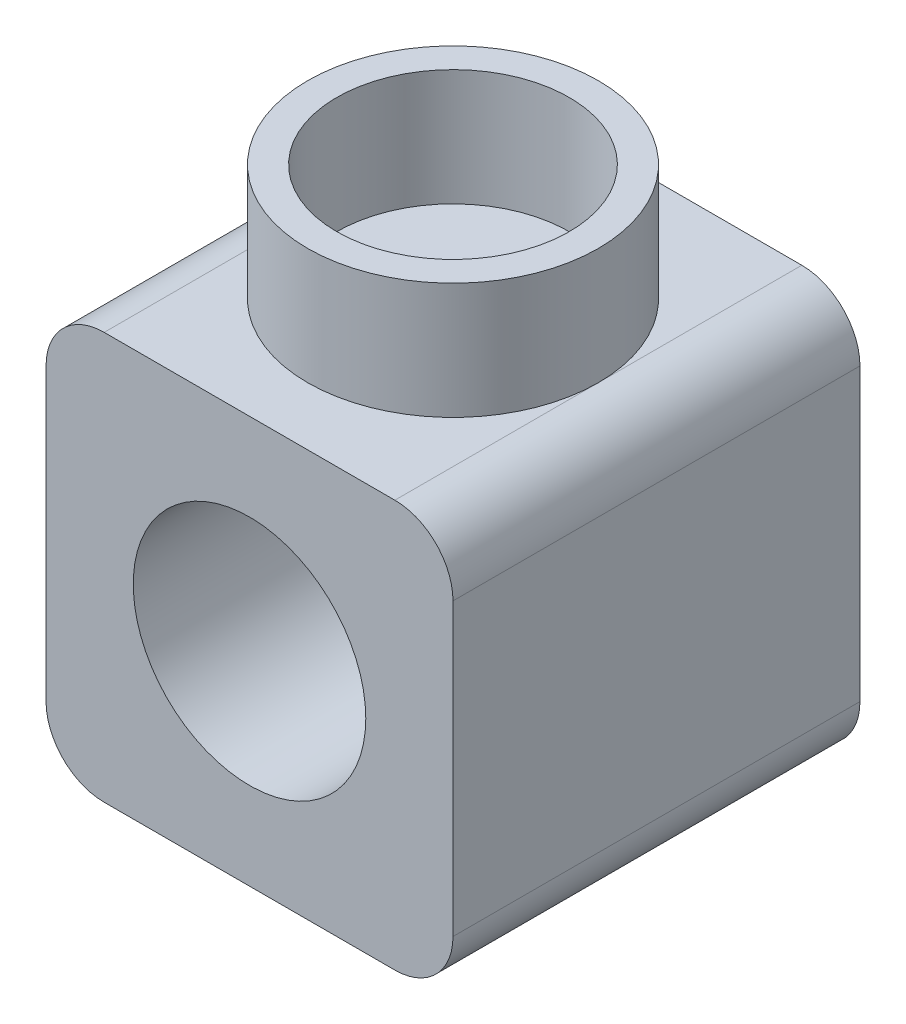
SolidWorks part; units mm, degrees
ref_plane "Front Plane" through (0, 0, 0) normal (0, 0, 1) x (1, 0, 0)
ref_plane "Top Plane" through (0, 0, 0) normal (0, 1, 0) x (1, 0, 0)
ref_plane "Right Plane" through (0, 0, 0) normal (1, 0, 0) x (0, 0, -1)
sketch "Sketch1" plane through (0, 0, 0) normal (0, 0, 1) x (1, 0, 0)
  line L1 (-125, 175) -> (125, 175)
  line L2 (-175, 125) -> (-175, -125)
  line L3 (-125, -175) -> (125, -175)
  line L4 (175, 125) -> (175, -125)
  line L5 (-175, 175) -> (175, -175) construction
  line L6 (-175, -175) -> (175, 175) construction
  circle A0 centre (0, 0) radius 100
  arc A1 (-125, -175) -> (-175, -125) centre (-125, -125) cw
  arc A2 (175, -125) -> (125, -175) centre (125, -125) cw
  arc A3 (125, 175) -> (175, 125) centre (125, 125) cw
  arc A4 (-125, 175) -> (-175, 125) centre (-125, 125) ccw
  point P0 (0, 0)
  dimension "D1" = 200
  dimension "D4" = 50
  dimension "D2" = 350
  dimension "D3" = 350
extrude "Boss-Extrude1" add sketch "Sketch1" along normal blind 350
sketch "Sketch2" plane through (0, 175, 0) normal (0, 1, 0) x (1, 0, 0)
  circle A0 centre (0, -175) radius 125
  circle A1 centre (0, -175) radius 100
  dimension "D1" = 250
  dimension "D2" = 200
extrude "Boss-Extrude2" add sketch "Sketch2" along normal blind 100
